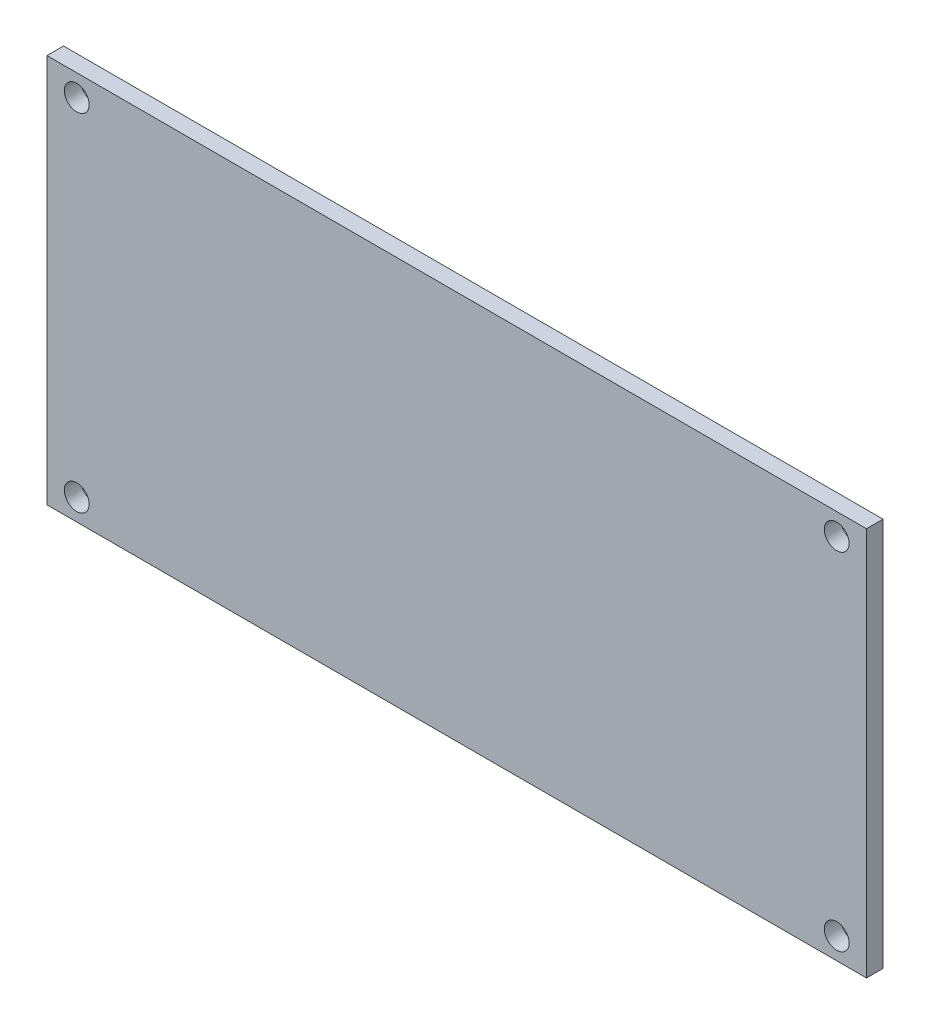
SolidWorks part; units mm, degrees
ref_plane "Спереди" through (0, 0, 0) normal (0, 0, 1) x (1, 0, 0)
ref_plane "Сверху" through (0, 0, 0) normal (0, 1, 0) x (1, 0, 0)
ref_plane "Справа" through (0, 0, 0) normal (1, 0, 0) x (0, 0, -1)
sketch "Эскиз1" plane through (0, 0, 0) normal (0, 0, 1) x (1, 0, 0)
  line L0 (-49.5, 17.2241) -> (-45.9, 17.2241) construction
  line L1 (-49.5, 23.5) -> (49.5, 23.5)
  line L2 (-49.5, 23.5) -> (-49.5, -23.5)
  line L3 (-49.5, -23.5) -> (49.5, -23.5)
  line L4 (49.5, 23.5) -> (49.5, -23.5)
  line L5 (-49.5, 23.5) -> (49.5, -23.5) construction
  line L6 (-49.5, -23.5) -> (49.5, 23.5) construction
  line L7 (-45.9, 23.5) -> (-45.9, 20.9) construction
  line L8 (0, 0) -> (-13.8481, 0) construction
  line L9 (0, 0) -> (0, 14.8145) construction
  circle A0 centre (-45.9, 20.9) radius 1.5
  circle A1 centre (45.9, 20.9) radius 1.5
  circle A2 centre (-45.9, -20.9) radius 1.5
  circle A3 centre (45.9, -20.9) radius 1.5
  point P0 (0, 0)
  dimension "D5" = 3
  dimension "D1" = 99
  dimension "D2" = 47
  dimension "D3" = 3.6
  dimension "D4" = 2.6
extrude "Бобышка-Вытянуть1" add sketch "Эскиз1" along normal blind 2
